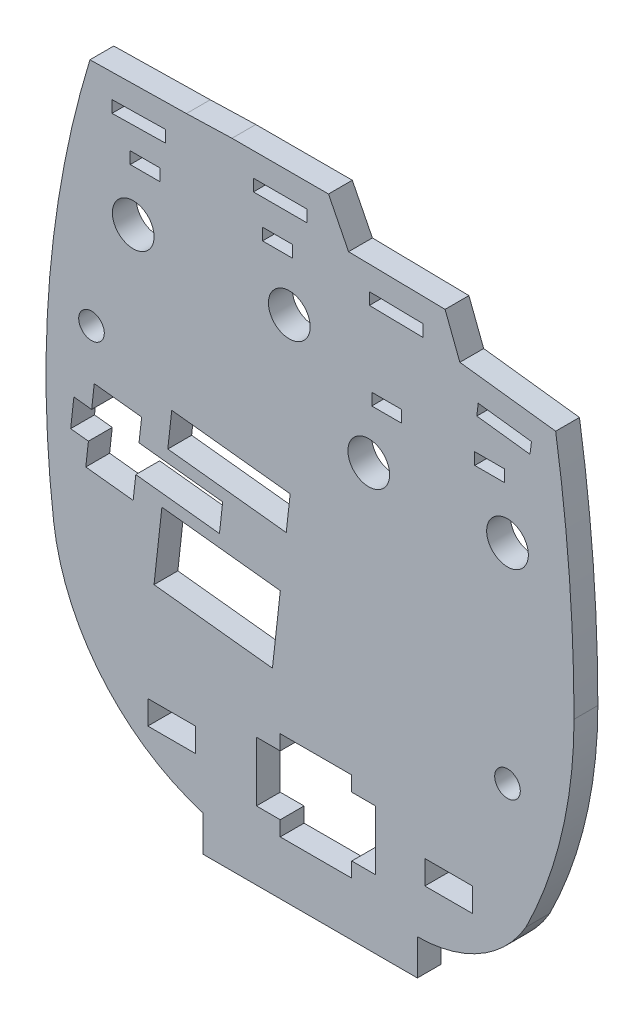
SolidWorks part; units mm, degrees
ref_plane "Front Plane" through (0, 0, 0) normal (0, 0, 1) x (1, 0, 0)
ref_plane "Top Plane" through (0, 0, 0) normal (0, 1, 0) x (1, 0, 0)
ref_plane "Right Plane" through (0, 0, 0) normal (1, 0, 0) x (0, 0, -1)
sketch "Sketch1" plane through (0, 0, 0) normal (0, 0, 1) x (1, 0, 0)
  line L0 (-4.5, 78.51) -> (-4.5, 76.51)
  line L1 (4.5, 78.51) -> (-4.5, 78.51)
  line L2 (-4.5, 76.51) -> (4.5, 76.51)
  line L3 (4.5, 76.51) -> (4.5, 78.51)
  line L4 (-4, -2.5) -> (0, -2.5)
  line L5 (0, 0) -> (19.57, 0) construction
  line L6 (0, 0) -> (0, 82.51) construction
  line L7 (12, 0) -> (0, 0)
  line L8 (0, 0) -> (-23.845, 0) construction
  line L9 (32.6473, 57.3216) -> (37.6473, 57.3216)
  line L10 (-12.9786, -18) -> (-12.9786, -24)
  line L11 (32.6473, 55.3216) -> (37.6473, 55.3216)
  line L12 (37.6473, 55.3216) -> (37.6473, 57.3216)
  line L13 (32.6473, 57.3216) -> (32.6473, 55.3216)
  line L14 (-28.275, 78.0626) -> (-19.2763, 78.2186)
  line L15 (-28.275, 78.0626) -> (-28.2403, 76.0629)
  line L16 (-28.2403, 76.0629) -> (-19.2416, 76.2189)
  line L17 (-19.2416, 76.2189) -> (-19.2763, 78.2186)
  line L18 (15.3631, 57.3216) -> (20.3631, 57.3216)
  line L19 (15.3631, 55.3216) -> (20.3631, 55.3216)
  line L20 (20.3631, 55.3216) -> (20.3631, 57.3216)
  line L21 (15.3631, 57.3216) -> (15.3631, 55.3216)
  line L22 (-2.9786, 72.1512) -> (2.0214, 72.1512)
  line L23 (15.0008, 71.7441) -> (14.9659, 69.7445)
  line L24 (14.9659, 69.7445) -> (23.9646, 69.5874)
  line L25 (-2.9786, 70.1512) -> (2.0214, 70.1512)
  line L26 (23.9995, 71.5871) -> (15.0008, 71.7441)
  line L27 (23.9646, 69.5874) -> (23.9995, 71.5871)
  line L28 (-23.845, 0) -> (-23.845, 82.14) construction
  line L29 (2.0214, 70.1512) -> (2.0214, 72.1512)
  line L30 (30.1504, 69.0671) -> (46.2296, 67.0929)
  line L31 (-2.9786, 72.1512) -> (-2.9786, 70.1512)
  line L32 (42.169, 63.5614) -> (33.236, 64.6582)
  line L33 (1.6675, 35.7056) -> (1.0057, 29.7422)
  line L34 (33.236, 64.6582) -> (32.9923, 62.6731)
  line L35 (-25.179, 72.1512) -> (-20.179, 72.1512)
  line L36 (19.57, 0) -> (19.57, 75.665) construction
  line L37 (0, 0) -> (38.19, 0) construction
  line L38 (-25.179, 70.1512) -> (-20.179, 70.1512)
  line L39 (32.9923, 62.6731) -> (41.9253, 61.5763)
  line L40 (-20.179, 70.1512) -> (-20.179, 72.1512)
  line L41 (-25.179, 72.1512) -> (-25.179, 70.1512)
  line L42 (41.9253, 61.5763) -> (42.169, 63.5614)
  line L43 (1.6675, 35.7056) -> (-18.2105, 37.9113)
  line L44 (0.0132, 20.7971) -> (-1.3102, 8.8703)
  line L45 (12, 0) -> (12, -2.5)
  line L46 (-18.8723, 31.9479) -> (1.0057, 29.7422)
  line L47 (12, -15) -> (0, -15)
  line L48 (-10.203, 23.9883) -> (-9.6615, 28.8683)
  line L49 (-35.1782, 26.7596) -> (-34.6367, 31.6396)
  line L50 (-9.6615, 28.8683) -> (-23.7053, 30.4266)
  line L51 (-32.6391, 22.4533) -> (-32.198, 26.4289)
  line L52 (-35.1782, 26.7596) -> (-32.198, 26.4289)
  line L53 (-24.2468, 25.5466) -> (-10.203, 23.9883)
  line L54 (-23.7053, 30.4266) -> (-23.2642, 34.4022)
  line L55 (-24.6879, 21.571) -> (-32.6391, 22.4533)
  line L56 (-18.8723, 31.9479) -> (-18.2105, 37.9113)
  line L57 (-31.2154, 35.2845) -> (-31.6565, 31.3089)
  line L58 (-23.2642, 34.4022) -> (-31.2154, 35.2845)
  line L59 (-31.6565, 31.3089) -> (-34.6367, 31.6396)
  line L60 (-24.6879, 21.571) -> (-24.2468, 25.5466)
  line L61 (-19.8648, 23.0028) -> (0.0132, 20.7971)
  line L62 (-21.1882, 11.076) -> (-1.3102, 8.8703)
  line L63 (0, -15) -> (0, -12.5)
  line L64 (-4, -12.5) -> (-4, -2.5)
  line L65 (-19.8648, 23.0028) -> (-21.1882, 11.076)
  line L66 (-12.9786, -24) -> (23.0214, -24)
  line L67 (-4, -12.5) -> (0, -12.5)
  line L68 (0, -2.5) -> (0, 0)
  line L69 (16, -12.5) -> (12, -12.5)
  line L70 (16, -12.5) -> (16, -2.5)
  line L71 (16, -2.5) -> (12, -2.5)
  line L72 (12, -12.5) -> (12, -15)
  line L73 (23.0214, -24) -> (23.0214, -18)
  line L74 (38.19, 0) -> (38.19, 68.08) construction
  line L75 (11.4712, 75.8064) -> (27.6688, 75.5236)
  line L76 (-8.1, 82.51) -> (8.1, 82.51)
  line L77 (-15.7462, 82.2805) -> (-31.9438, 81.9995)
  line L78 (30.1504, 69.0671) -> (27.6688, 75.5236)
  line L79 (-9.9323, 26.4283) -> (3.8676, 24.897) construction
  line L80 (41.2436, -7.5) -> (16, -7.5) construction
  line L81 (11.4712, 75.8064) -> (8.1, 82.51)
  line L82 (-8.1, 82.51) -> (-15.7462, 82.2805)
  line L83 (-35.1782, 26.7596) -> (49.3139, 26.7596) construction
  line L84 (37.7025, 64.1098) -> (38.19, 68.08) construction
  line L85 (38.1473, 11.8216) -> (-38.0327, 11.8216) construction
  line L86 (-18.8723, 31.9479) -> (-19.8648, 23.0028) construction
  line L87 (-19.3685, 27.4754) -> (-39.2913, 29.686) construction
  line L88 (19.5002, 71.6656) -> (19.57, 75.665) construction
  line L89 (-23.7756, 78.1406) -> (-23.845, 82.14) construction
  line L90 (0, 78.51) -> (0, 82.51) construction
  line L91 (38.1473, 46.8216) -> (38.1473, 11.8216) construction
  arc A0 (23.0214, -18) -> (41.2436, -7.5) centre (23.0214, 3.0618) ccw
  circle A1 centre (38.1473, 11.8216) radius 2.15
  arc A2 (-38.0327, 11.8216) -> (-31.9438, 81.9995) centre (129.7414, 32.618) cw
  circle A3 centre (-24.679, 61.6512) radius 3.5
  circle A4 centre (1.5214, 61.6512) radius 3.5
  circle A5 centre (14.8631, 46.8216) radius 3.5
  circle A6 centre (38.1473, 46.8216) radius 3.5
  arc A7 (-38.0327, 11.8216) -> (-12.9786, -18) centre (-2.5175, 16.2239) ccw
  circle A8 centre (-31.6815, 43.4564) radius 2.15
  circle A9 centre (-14, -9.1244) radius 2.15 construction
  arc A10 (49.3139, 26.7596) -> (41.2436, -7.5) centre (-27.4393, 26.7596) cw
  arc A11 (49.3139, 26.7596) -> (46.2296, 67.0929) centre (-215.9488, 26.7596) ccw
  dimension "D1" = 7
  dimension "D2" = 4.3
  dimension "D10" = 1.0057
  dimension "D11" = 1.5214
  dimension "D22" = 14.8631
  dimension "D28" = 23.0214
  dimension "D35" = 38.1473
  dimension "D40" = 9.6615
  dimension "D41" = 10.203
  dimension "D42" = 12.9786
  dimension "D43" = 14
  dimension "D50" = 24.679
  dimension "D52" = 31.6815
  dimension "D60" = 43.4564
  dimension "D61" = 46.8216
  dimension "D65" = 61.6512
  dimension "D72" = 9.1244
  dimension "D13" = 82.51
  dimension "D15" = 23.845
  dimension "D16" = 82.14
  dimension "D17" = 19.57
  dimension "D20" = 38.19
  dimension "D26" = 16.2
  dimension "D27" = 5
  dimension "D29" = 55.3216
  dimension "D30" = 32.6473
  dimension "D32" = 15.3631
  dimension "D33" = 70.1512
  dimension "D36" = 2.9786
  dimension "D39" = 25.179
  dimension "D53" = 9.0001
  dimension "D46" = 4
  dimension "D48" = 4
  dimension "D19" = 75.665
  dimension "D62" = 2
  dimension "D59" = 21.571
  dimension "D21" = 18
  dimension "D23" = 68.08
  dimension "D37" = 4
  dimension "D47" = 57.3216
  dimension "D57" = 72.1512
  dimension "D45" = 20
  dimension "D49" = 4.5
  dimension "D51" = 25.1285
  dimension "D54" = 8
  dimension "D56" = 14.13
  dimension "D9" = 9
  dimension "D12" = 6
  dimension "D38" = 4.91
  dimension "D8" = 12
  dimension "D14" = 10
  dimension "D18" = 2.5
  dimension "D24" = 4
  dimension "ThumbLinkLengthMCP" = 20.045
  dimension "D25" = 4
  dimension "D34" = 8.1
  dimension "D44" = 35
extrude "Boss-Extrude1" add sketch "Sketch1" along normal blind 4
sketch "Sketch2" plane through (0, 0, 0) normal (0, 0, -1) x (-1, 0, 0)
  line L0 (-5.0214, -24) -> (-5.0214, -5.2587) construction
  line L1 (-24.2714, -10) -> (-32.2714, -10)
  line L2 (-32.2714, -10) -> (-32.2714, -6)
  line L3 (-32.2714, -6) -> (-24.2714, -6)
  line L4 (-24.2714, -6) -> (-24.2714, -10)
  line L5 (12.9786, -24) -> (-23.0214, -24) construction
  line L6 (14.2286, -6) -> (14.2286, -10)
  line L7 (22.2286, -6) -> (14.2286, -6)
  line L8 (22.2286, -10) -> (22.2286, -6)
  line L9 (14.2286, -10) -> (22.2286, -10)
  dimension "D1" = 4
  dimension "D2" = 8
  dimension "D3" = 19.25
  dimension "D4" = 14
extrude "Cut-Extrude1" cut sketch "Sketch2" against normal through all
equation "\"D13@Sketch1\"= \"HL@parametersSketch@prostheticParameters.SLDPRT\" * 0.446'Middle Base Frame"
equation "\"D15@Sketch1\"= \"HB@parametersSketch@prostheticParameters.SLDPRT\" * 0.251'Index Base Frame X"
equation "\"D16@Sketch1\"= \"HL@parametersSketch@prostheticParameters.SLDPRT\" * 0.444'Index Base Frame Y"
equation "\"D17@Sketch1\"= \"HB@parametersSketch@prostheticParameters.SLDPRT\" * 0.206'Ring Base Frame X"
equation "\"D19@Sketch1\"= \"HL@parametersSketch@prostheticParameters.SLDPRT\" * 0.409'Ring base Frame Y"
equation "\"D20@Sketch1\"= \"HB@parametersSketch@prostheticParameters.SLDPRT\" * 0.402'Pinky Base Frame X"
equation "\"D23@Sketch1\"= \"HL@parametersSketch@prostheticParameters.SLDPRT\" * 0.368'Pinky Base Frame Y"
equation "\"D26@Sketch1\"= \"fingerWidth@parametersSketch@prostheticParameters.SLDPRT\"'Fingers Width"
equation "\"D59@Sketch1\"= \"HL@parametersSketch@prostheticParameters.SLDPRT\" * 0.1166'Hole Thumb Y"
equation "\"D40@Sketch1\"= \"HB@parametersSketch@prostheticParameters.SLDPRT\" * 0.1017'Hole Thumb X1"
equation "\"D41@Sketch1\"= \"HB@parametersSketch@prostheticParameters.SLDPRT\" * 0.1074'Hole Thumb X2"
equation "\"ThumbLinkLengthMCP@Sketch1\"= \"HB@parametersSketch@prostheticParameters.SLDPRT\" * 0.211"
equation "\"D53@Sketch1\"= \"fingerWidth@parametersSketch@prostheticParameters.SLDPRT\" * 0.55556"
equation "\"D34@Sketch1\"= \"fingerWidth@parametersSketch@prostheticParameters.SLDPRT\" / 2"
equation "\"D2@Sketch1\"= 4 + \"tol1@parametersSketch@prostheticParameters.SLDPRT\""
